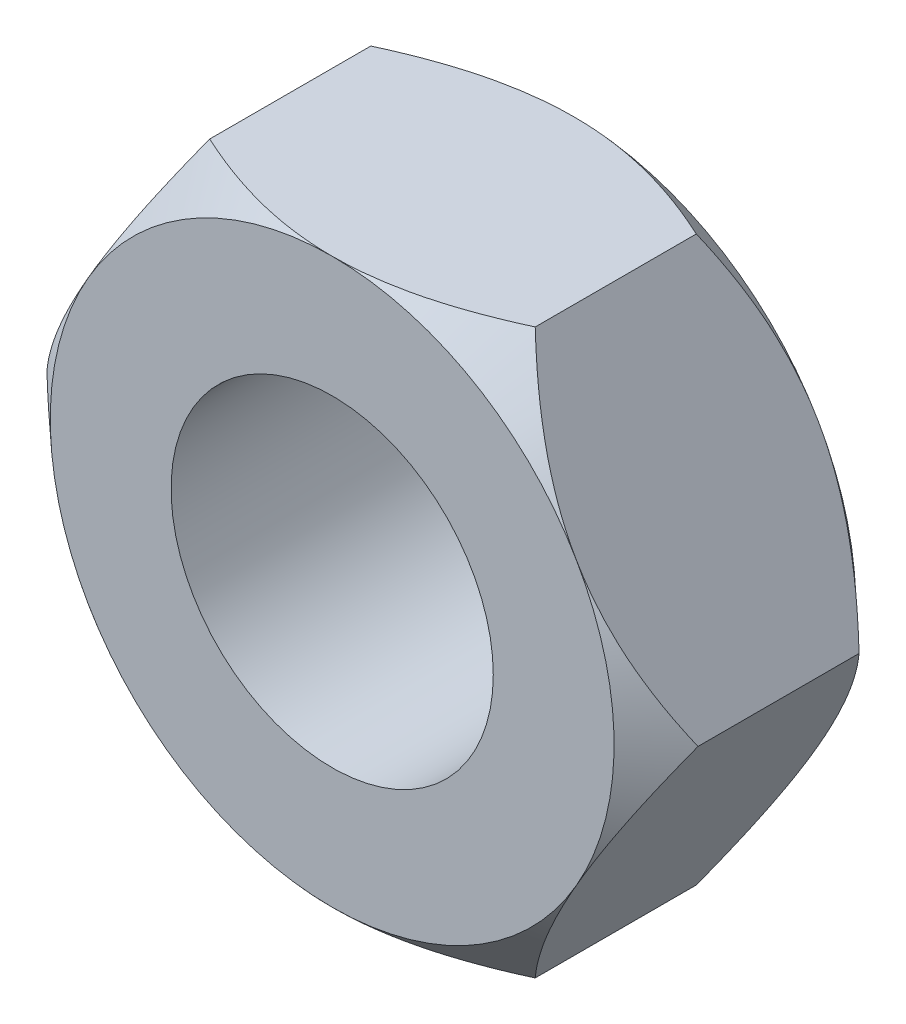
SolidWorks part; units mm, degrees
ref_plane "Front Plane" through (0, 0, 0) normal (0, 0, 1) x (1, 0, 0)
ref_plane "Top Plane" through (0, 0, 0) normal (0, 1, 0) x (1, 0, 0)
ref_plane "Right Plane" through (0, 0, 0) normal (1, 0, 0) x (0, 0, -1)
sketch "Sketch1" plane through (0, 0, 0) normal (0, 0, 1) x (1, 0, 0)
  line L1 (2.0207, -3.5) -> (4.0415, 0)
  line L2 (4.0415, 0) -> (2.0207, 3.5)
  line L3 (2.0207, 3.5) -> (-2.0207, 3.5)
  line L4 (-2.0207, 3.5) -> (-4.0415, 0)
  line L5 (-4.0415, 0) -> (-2.0207, -3.5)
  line L6 (-2.0207, -3.5) -> (2.0207, -3.5)
  circle A0 centre (0, 0) radius 3.5 construction
  circle A1 centre (0, 0) radius 2
  point P10 (3.1974, 2.4719)
  dimension "D2" = 4
  dimension "D1" = 7
extrude "Boss-Extrude1" add sketch "Sketch1" along normal blind 3 contours L5 L6 L1 L2 L3 L4 A1
sketch "Sketch3" plane through (0, 0, 0) normal (0, 1, 0) x (1, 0, 0)
  line L0 (0, 0) -> (0, -3.9323) construction
  line L1 (4.0415, -3) -> (4.0415, -2.5)
  line L2 (4.0415, -3) -> (4.0415, 0) construction
  line L3 (4.0415, -2.5) -> (3.5, -3)
  line L4 (4.0415, -3) -> (2.0207, -3) construction
  line L5 (3.5, -3) -> (4.0415, -3)
  line L6 (2.0207, -1.5) -> (-2.0207, -1.5) construction
  line L7 (2.0207, -3) -> (2.0207, 0) construction
  line L8 (-2.0207, -3) -> (-2.0207, 0) construction
  line L9 (3.5, 0) -> (4.0415, 0)
  line L10 (4.0415, -0.5) -> (3.5, 0)
  line L11 (4.0415, 0) -> (4.0415, -0.5)
  dimension "D1" = 7
  dimension "D2" = 2
revolve "Cut-Revolve1" cut sketch "Sketch3" angle 360 about L0
